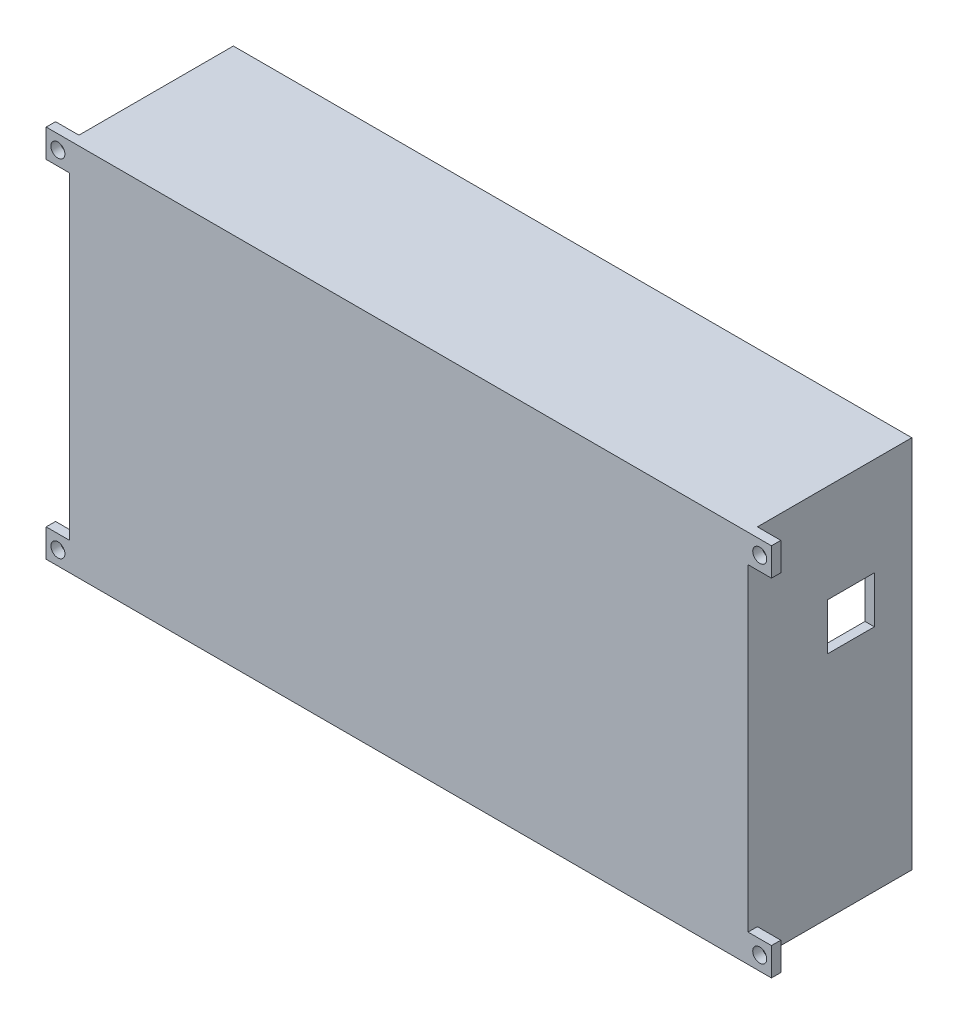
SolidWorks part; units mm, degrees
ref_plane "Спереди" through (0, 0, 0) normal (0, 0, 1) x (1, 0, 0)
ref_plane "Сверху" through (0, 0, 0) normal (0, 1, 0) x (1, 0, 0)
ref_plane "Справа" through (0, 0, 0) normal (1, 0, 0) x (0, 0, -1)
sketch "Эскиз1" plane through (0, 0, 0) normal (0, 0, 1) x (1, 0, 0)
  line L1 (0, 0) -> (145, 0)
  line L2 (0, 0) -> (0, 80)
  line L3 (0, 80) -> (145, 80)
  line L4 (145, 0) -> (145, 80)
  dimension "D1" = 145
  dimension "D2" = 80
extrude "Бобышка-Вытянуть1" add sketch "Эскиз1" along normal blind 35
sketch "Эскиз2" plane through (0, 0, 0) normal (0, 0, -1) x (-1, 0, 0)
  line L0 (-145, 0) -> (-145, 80) construction
  line L1 (-143, 2) -> (-2, 2)
  line L2 (-143, 2) -> (-143, 78)
  line L3 (-143, 78) -> (-2, 78)
  line L4 (-2, 2) -> (-2, 78)
  line L5 (0, 0) -> (-145, 0) construction
  line L6 (0, 80) -> (0, 0) construction
  line L7 (-145, 80) -> (0, 80) construction
  dimension "D1" = 2
  dimension "D2" = 2
  dimension "D3" = 2
  dimension "D4" = 2
extrude "Вырез-Вытянуть1" cut sketch "Эскиз2" against normal blind 33
sketch "Эскиз3" plane through (0, 0, 33) normal (0, 0, -1) x (-1, 0, 0)
  line L0 (-143, 40) -> (3.9467, 40) construction
  line L1 (-143, 78) -> (-143, 2) construction
  line L3 (-143, 78) -> (-143, 2) construction
  circle A0 centre (-109.79, 62.86) radius 3.5
  circle A1 centre (-109.79, 17.14) radius 3.5
  circle A2 centre (-34.79, 64.13) radius 3.5
  circle A3 centre (-34.79, 15.87) radius 3.5
  point P8 (-202.8123, 30.4132)
  point P9 (0, 0)
  point P14 (0, 0)
  point P15 (0, 0)
  dimension "D1" = 7
  dimension "D2" = 7
  dimension "D4" = 7
  dimension "D5" = 7
  dimension "D3" = 45.72
  dimension "D6" = 48.26
  dimension "D7" = 75
  dimension "D8" = 33.21
extrude "Бобышка-Вытянуть2" add sketch "Эскиз3" along normal blind 15
sketch "Эскиз4" plane through (0, 0, 18) normal (0, 0, -1) x (-1, 0, 0)
  circle A0 centre (-109.79, 62.86) radius 1.5
  circle A1 centre (-34.79, 64.13) radius 1.5
  circle A2 centre (-34.79, 15.87) radius 1.5
  circle A3 centre (-109.79, 17.14) radius 1.5
  point P5 (-34.79, 59.13)
  point P9 (-34.79, 10.87)
  point P13 (-109.79, 12.14)
  point P15 (0, 0)
  dimension "D1" = 3
  dimension "D2" = 3
  dimension "D3" = 3
  dimension "D4" = 3
extrude "Вырез-Вытянуть2" cut sketch "Эскиз4" against normal blind 15
sketch "Эскиз5" plane through (0, 0, 0) normal (-1, 0, 0) x (0, 0, 1)
  line L1 (8, 31) -> (18, 31)
  line L2 (8, 31) -> (8, 21)
  line L3 (8, 21) -> (18, 21)
  line L4 (18, 31) -> (18, 21)
  line L5 (35, 80) -> (35, 0) construction
  line L6 (35, 0) -> (0, 0) construction
  line L9 (35, 80) -> (0, 80) construction
  line L10 (6, 62) -> (22, 62)
  line L11 (6, 62) -> (6, 41)
  line L12 (6, 41) -> (22, 41)
  line L13 (22, 62) -> (22, 41)
  point P4 (18, 26)
  dimension "D1" = 10
  dimension "D2" = 10
  dimension "D3" = 21
  dimension "D4" = 17
  dimension "D5" = 21
  dimension "D6" = 16
  dimension "D7" = 18
  dimension "D8" = 13
extrude "Вырез-Вытянуть3" cut sketch "Эскиз5" against normal blind 15
sketch "Эскиз6" plane through (143, 0, 0) normal (-1, 0, 0) x (0, 0, 1)
  line L0 (35, 80) -> (0, 80) construction
  line L1 (8, 59) -> (18, 59)
  line L2 (8, 59) -> (8, 49)
  line L3 (8, 49) -> (18, 49)
  line L4 (18, 59) -> (18, 49)
  line L6 (35, 0) -> (35, 80) construction
  dimension "D1" = 10
  dimension "D2" = 10
  dimension "D3" = 21
  dimension "D4" = 17
extrude "Вырез-Вытянуть4" cut sketch "Эскиз6" against normal blind 15
sketch "Эскиз9" plane through (0, 0, 33) normal (0, 0, -1) x (-1, 0, 0)
  line L1 (-2, 78) -> (-143, 78) construction
  line L3 (-2, 2) -> (-2, 78) construction
  circle A0 centre (-4, 76) radius 3.5
  point P2 (-12.2933, 76)
  point P6 (0, 0)
  point P8 (-0.4066, 75.4728)
  dimension "D1" = 7
  dimension "D2" = 2
  dimension "D3" = 2
extrude "Бобышка-Вытянуть3" add sketch "Эскиз9" along normal blind 33
sketch "Эскиз10" plane through (0, 0, 0) normal (0, 0, -1) x (-1, 0, 0)
  circle A0 centre (-4, 76) radius 1.5
  arc A1 (-6.8723, 78) -> (-2, 73.1277) centre (-4, 76) ccw construction
  point P2 (-3.9594, 75.8316)
  point P3 (0, 0)
  point P4 (-3.9298, 75.7614)
  dimension "D1" = 3
  dimension "D2" = 0
extrude "Вырез-Вытянуть5" cut sketch "Эскиз10" against normal blind 33
pattern_linear "Линейный массив2" count 2 spacing 72 along (0, -1, 0) count 2 spacing 137 along (1, 0, 0) of "Вырез-Вытянуть5", "Бобышка-Вытянуть3"
sketch "Эскиз12" plane through (145, 0, 0) normal (1, 0, 0) x (0, 0, -1)
  line L0 (-35, 0) -> (-35, 80) construction
  line L1 (-35, 74) -> (-33, 74)
  line L2 (-35, 74) -> (-35, 80)
  line L3 (-35, 80) -> (-33, 80)
  line L4 (-33, 74) -> (-33, 80)
  line L5 (-35, 80) -> (0, 80) construction
  line L6 (-35, 0) -> (0, 0) construction
  line L7 (-35, 6) -> (-33, 6)
  line L8 (-35, 6) -> (-35, 0)
  line L9 (-35, 0) -> (-33, 0)
  line L10 (-33, 6) -> (-33, 0)
  dimension "D1" = 6
  dimension "D2" = 2
  dimension "D3" = 6
  dimension "D4" = 2
extrude "Бобышка-Вытянуть4" add sketch "Эскиз12" along normal blind 5
sketch "Эскиз13" plane through (0, 0, 33) normal (0, 0, -1) x (-1, 0, 0)
  line L0 (-150, 74) -> (-145, 74) construction
  line L1 (-150, 74) -> (-150, 80) construction
  circle A0 centre (-147.5, 77) radius 1.5
  dimension "D1" = 3
  dimension "D2" = 3
  dimension "D3" = 2.5
extrude "Вырез-Вытянуть6" cut sketch "Эскиз13" against normal blind 5
pattern_linear "Линейный массив3" count 2 spacing 74 along (0, -1, 0) of "Вырез-Вытянуть6"
pattern_linear "Линейный массив4" count 2 spacing 150 along (-1, 0, 0) of "Линейный массив3", "Бобышка-Вытянуть4", "Вырез-Вытянуть6"
